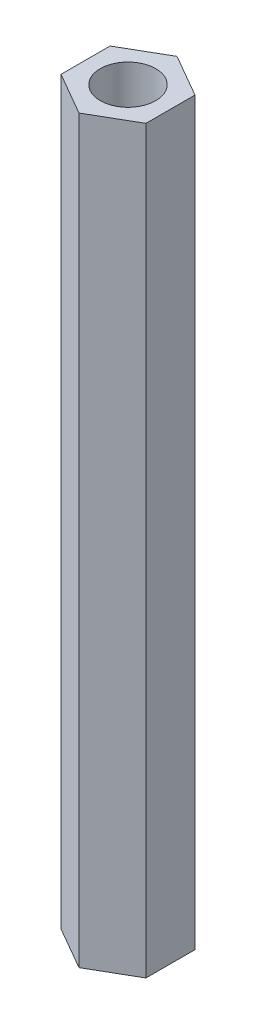
SolidWorks part; units mm, degrees
ref_plane "Front Plane" through (0, 0, 0) normal (0, 0, 1) x (1, 0, 0)
ref_plane "Top Plane" through (0, 0, 0) normal (0, 1, 0) x (1, 0, 0)
ref_plane "Right Plane" through (0, 0, 0) normal (1, 0, 0) x (0, 0, -1)
sketch "Sketch2" plane through (0, 0, 0) normal (0, 1, 0) x (1, 0, 0)
  line L1 (0, 2.65) -> (-2.295, 1.325)
  line L2 (-2.295, 1.325) -> (-2.295, -1.325)
  line L3 (-2.295, -1.325) -> (0, -2.65)
  line L4 (0, -2.65) -> (2.295, -1.325)
  line L5 (2.295, -1.325) -> (2.295, 1.325)
  line L6 (2.295, 1.325) -> (0, 2.65)
  circle A0 centre (0, 0) radius 2.295 construction
  circle A1 centre (0, 0) radius 1.5
extrude "Boss-Extrude1" add sketch "Sketch2" along normal blind 40
